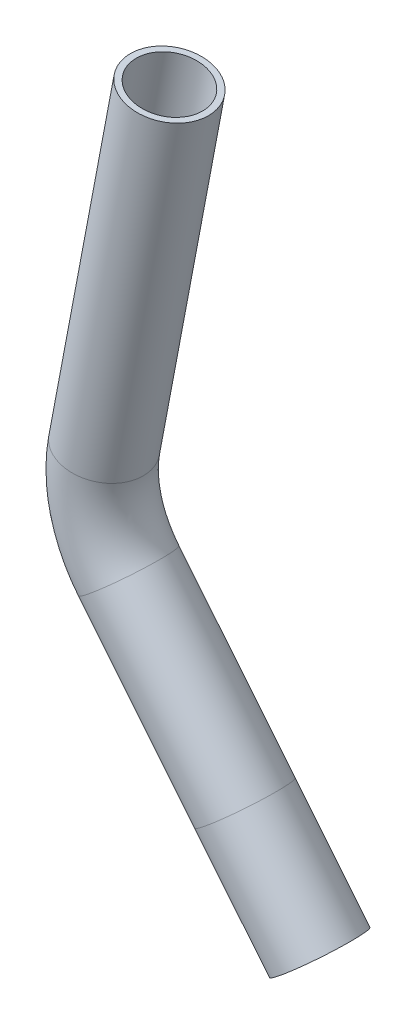
SolidWorks part; units mm, degrees
ref_plane "Спереди" through (0, 0, 0) normal (0, 0, 1) x (1, 0, 0)
ref_plane "Сверху" through (0, 0, 0) normal (0, 1, 0) x (1, 0, 0)
ref_plane "Справа" through (0, 0, 0) normal (1, 0, 0) x (0, 0, -1)
sketch "Эскиз1" plane through (0, 0, 0) normal (0, 0, 1) x (1, 0, 0)
  line L0 (-6.3059, 7.7611) -> (-16.1072, 19.8242)
  line L1 (-18.1715, 27.9903) -> (-12.6706, 57.0465)
  line L2 (-6.3059, 7.7611) -> (0, 0)
  arc A0 (-16.1072, 19.8242) -> (-18.1715, 27.9903) centre (-8.346, 26.1302) cw
  dimension "D1" = 10
ref_plane "Плоскость1" through (0, 0, 0) normal (0.6306, -0.7761, 0) x (-0.7761, -0.6306, 0)
sketch "Эскиз2" plane through (0, 0, 0) normal (0.6306, -0.7761, 0) x (-0.7761, -0.6306, 0)
  circle A0 centre (0, 0) radius 3.35
  circle A1 centre (0, 0) radius 2.85
  dimension "D1" = 6.7
  dimension "D2" = 5.7
sweep "По траектории1" add profiles "Эскиз2" path "Эскиз1"
